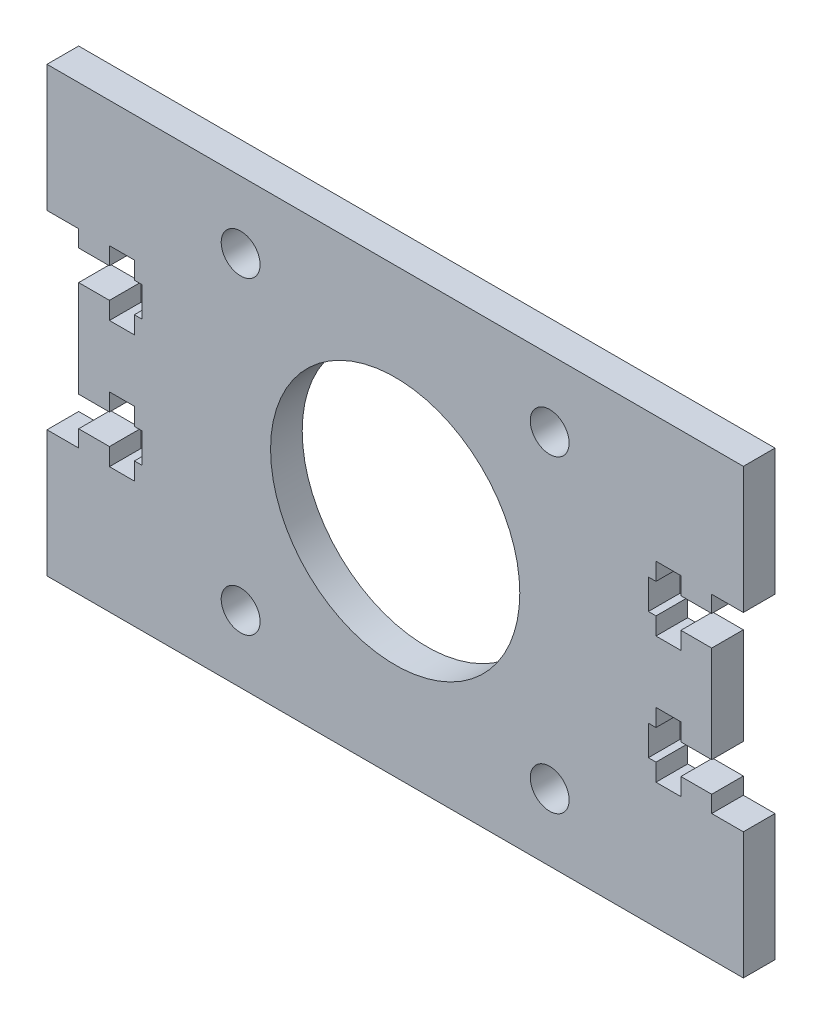
SolidWorks part; units mm, degrees
ref_plane "Front Plane" through (0, 0, 0) normal (0, 0, 1) x (1, 0, 0)
ref_plane "Top Plane" through (0, 0, 0) normal (0, 1, 0) x (1, 0, 0)
ref_plane "Right Plane" through (0, 0, 0) normal (1, 0, 0) x (0, 0, -1)
sketch "Sketch2" plane through (0, 0, 0) normal (0, 0, 1) x (1, 0, 0)
  line L0 (0, 22.225) -> (63.5, 22.225) construction
  line L1 (0, 0) -> (63.5, 0)
  line L2 (0, 12.7) -> (0, 14.375)
  line L3 (0, 44.45) -> (63.5, 44.45)
  line L4 (63.5, 0) -> (63.5, 44.45)
  line L5 (31.75, 44.45) -> (31.75, 0) construction
  line L6 (5.588, 30.075) -> (5.588, 31.825)
  line L7 (0, 0) -> (-3.175, 0)
  line L8 (0, 17.375) -> (0, 31.75)
  line L9 (0, 12.7) -> (-3.175, 12.7)
  line L10 (-3.175, 0) -> (-3.175, 12.7)
  line L11 (0, 17.375) -> (3.088, 17.375)
  line L12 (3.088, 14.375) -> (3.088, 12.625)
  line L13 (0, 14.375) -> (3.088, 14.375)
  line L14 (6.35, 17.375) -> (6.35, 14.375)
  line L15 (60.412, 14.375) -> (60.412, 12.625)
  line L16 (3.088, 19.125) -> (5.588, 19.125)
  line L17 (3.088, 19.125) -> (3.088, 17.375)
  line L18 (3.088, 12.625) -> (5.588, 12.625)
  line L19 (5.588, 19.125) -> (5.588, 17.375)
  line L20 (57.912, 27.075) -> (57.15, 27.075)
  line L21 (5.588, 14.375) -> (5.588, 12.625)
  line L22 (57.912, 30.075) -> (57.912, 31.825)
  line L23 (57.912, 30.075) -> (57.15, 30.075)
  line L24 (5.588, 25.325) -> (5.588, 27.075)
  line L25 (3.088, 31.825) -> (5.588, 31.825)
  line L26 (3.088, 25.325) -> (3.088, 27.075)
  line L27 (3.088, 25.325) -> (5.588, 25.325)
  line L28 (6.35, 27.075) -> (6.35, 30.075)
  line L29 (0, 30.075) -> (3.088, 30.075)
  line L30 (5.588, 17.375) -> (6.35, 17.375)
  line L31 (0, 27.075) -> (3.088, 27.075)
  line L32 (-3.175, 44.45) -> (-3.175, 31.75)
  line L33 (0, 31.75) -> (-3.175, 31.75)
  line L34 (5.588, 30.075) -> (6.35, 30.075)
  line L35 (0, 44.45) -> (-3.175, 44.45)
  line L42 (63.5, 44.45) -> (66.675, 44.45)
  line L43 (5.588, 14.375) -> (6.35, 14.375)
  line L44 (63.5, 31.75) -> (66.675, 31.75)
  line L45 (66.675, 44.45) -> (66.675, 31.75)
  line L46 (63.5, 27.075) -> (60.412, 27.075)
  line L47 (57.912, 14.375) -> (57.15, 14.375)
  line L48 (63.5, 30.075) -> (60.412, 30.075)
  line L49 (57.15, 27.075) -> (57.15, 30.075)
  line L50 (60.412, 25.325) -> (57.912, 25.325)
  line L51 (60.412, 25.325) -> (60.412, 27.075)
  line L52 (60.412, 31.825) -> (57.912, 31.825)
  line L53 (57.912, 25.325) -> (57.912, 27.075)
  line L54 (57.912, 19.125) -> (57.912, 17.375)
  line L55 (60.412, 12.625) -> (57.912, 12.625)
  line L56 (60.412, 19.125) -> (60.412, 17.375)
  line L57 (60.412, 19.125) -> (57.912, 19.125)
  line L58 (57.15, 17.375) -> (57.15, 14.375)
  line L59 (63.5, 14.375) -> (60.412, 14.375)
  line L60 (5.588, 27.075) -> (6.35, 27.075)
  line L61 (63.5, 17.375) -> (60.412, 17.375)
  line L62 (66.675, 0) -> (66.675, 12.7)
  line L63 (63.5, 12.7) -> (66.675, 12.7)
  line L64 (3.088, 30.075) -> (3.088, 31.825)
  line L65 (63.5, 0) -> (66.675, 0)
  line L66 (57.912, 14.375) -> (57.912, 12.625)
  line L67 (57.912, 17.375) -> (57.15, 17.375)
  line L70 (60.412, 30.075) -> (60.412, 31.825)
  circle A0 centre (16.25, 37.725) radius 1.95
  circle A1 centre (47.25, 37.725) radius 1.95
  circle A2 centre (47.25, 6.725) radius 1.95
  circle A3 centre (16.25, 6.725) radius 1.95
  circle A4 centre (31.75, 22.225) radius 12.5
  point P28 (4.338, 15.875)
  point P46 (4.338, 28.575)
  point P73 (59.162, 28.575)
  point P74 (59.162, 15.875)
  dimension "D3" = 3.9
  dimension "D6" = 25
  dimension "D1" = 44.45
  dimension "D2" = 63.5
  dimension "D4" = 31
  dimension "D5" = 31
  dimension "D7" = 3.175
  dimension "D8" = 12.7
  dimension "D9" = 0.762
  dimension "D10" = 2.5
  dimension "D11" = 6.35
  dimension "D12" = 3
  dimension "D13" = 6.5
extrude "Boss-Extrude1" add sketch "Sketch2" along normal blind 3.175 contours L70 L48 L4 L3 L35 L32 L33 L8 L29 L64 L25 L6 L34 L28 L60 L24 L27 L26 L31 L11 L17 L16 L19 L30 L14 L43 L21 L18 L12 L13 L2 L9 L10 L7 L1 L59 L15 L55 L66 L47 L58 L67 L54 L57 L56 L61 | L4 L65 L62 L63 | L45 L42 L4 L44 | A4
